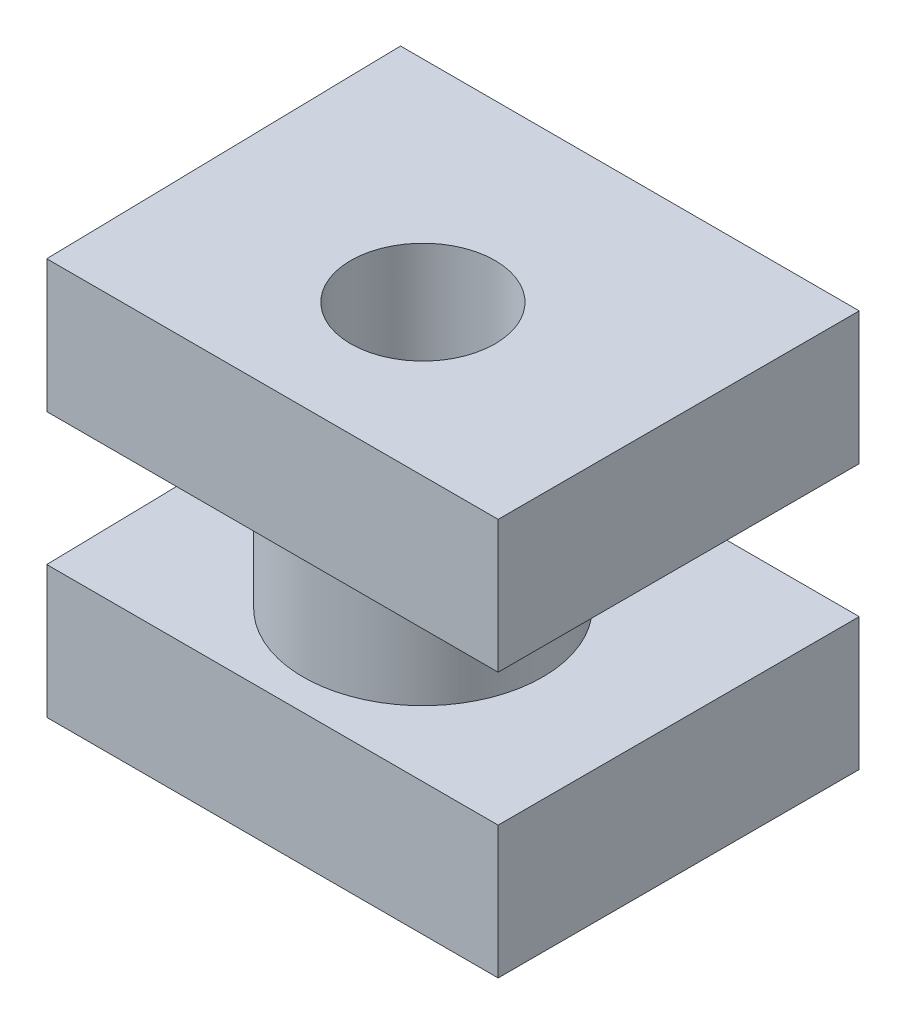
SolidWorks part; units mm, degrees
material "Silicon Rubber"
ref_plane "Front Plane" through (0, 0, 0) normal (0, 0, 1) x (1, 0, 0)
ref_plane "Top Plane" through (0, 0, 0) normal (0, 1, 0) x (1, 0, 0)
ref_plane "Right Plane" through (0, 0, 0) normal (1, 0, 0) x (0, 0, -1)
sketch "Sketch1" plane through (0, 0, 0) normal (0, 1, 0) x (1, 0, 0)
  line L0 (-5.035, 1.3939) -> (-5.035, 3.2473)
  line L1 (-5.035, 3.2473) -> (-7.6675, 3.2473) construction
  line L2 (-5.035, 3.2473) -> (-2.8, 3.2473)
  line L8 (-0.1675, 3.2473) -> (-2.8, 3.2473) construction
  line L9 (-2.8, 3.2473) -> (-2.8, 1.3939)
  line L10 (-3.9175, -0.2527) -> (-3.9175, 3.2473) construction
  line L11 (-0.1675, -2.7527) -> (-0.1675, 3.2473) construction
  line L12 (-7.6675, -2.7527) -> (-7.6675, 3.2473) construction
  line L13 (-0.1675, -2.7527) -> (-7.6675, -2.7527) construction
  line L14 (-7.6675, -0.2527) -> (-7.6675, 3.2473) construction
  line L15 (-5.035, -2.7527) -> (-8.015, -2.7527) construction
  line L16 (-0.1675, -0.2527) -> (-0.1675, 3.2473) construction
  line L18 (-5.035, 3.2473) -> (-8.015, 3.2473) construction
  arc A0 (-5.035, 1.3939) -> (-2.8, 1.3939) centre (-3.9175, -0.2527) ccw
  circle A1 centre (-3.9175, -0.2527) radius 1.2
  dimension "D1" = 3.75
  dimension "D2" = 3.75
  dimension "D3" = 6
extrude "Boss-Extrude1" add sketch "Sketch1" along normal blind 2.2
sketch "Sketch2" plane through (0, 0, 0) normal (0, -1, 0) x (1, 0, 0)
  line L0 (-3.9175, -3.2473) -> (-0.1675, -3.2473)
  line L1 (-2.8, -3.2473) -> (-5.035, -3.2473) construction
  line L2 (-0.1675, -3.2473) -> (-0.1675, 2.7527)
  line L3 (-0.1675, 2.7527) -> (-7.6675, 2.7527)
  line L4 (-7.6675, 2.7527) -> (-7.7899, -3.2473)
  line L5 (-3.9175, -3.2473) -> (-7.7899, -3.2473)
  circle A0 centre (-3.9175, 0.2527) radius 1.2 construction
  circle A1 centre (-3.9175, 0.2527) radius 1.2
extrude "Boss-Extrude2" add sketch "Sketch2" along normal blind 2.2
sketch "Sketch3" plane through (0, 2.2, 0) normal (0, 1, 0) x (1, 0, 0)
  line L0 (-7.7899, 3.2473) -> (-5.035, 3.2473) construction
  line L1 (-7.7899, 3.2473) -> (-5.035, 3.2473)
  line L2 (-7.6675, -2.7527) -> (-7.7899, 3.2473) construction
  line L3 (-7.6675, -2.7527) -> (-7.7899, 3.2473)
  line L4 (-0.1675, -2.7527) -> (-7.6675, -2.7527) construction
  line L5 (-0.1675, -2.7527) -> (-7.6675, -2.7527)
  line L6 (-0.1675, 3.2473) -> (-0.1675, -2.7527) construction
  line L7 (-0.1675, 3.2473) -> (-0.1675, -2.7527)
  line L8 (-2.8, 3.2473) -> (-0.1675, 3.2473) construction
  line L9 (-2.8, 3.2473) -> (-0.1675, 3.2473)
  line L10 (-2.8, 3.2473) -> (-5.035, 3.2473) construction
  line L11 (-2.8, 3.2473) -> (-5.035, 3.2473)
  circle A0 centre (-3.9175, -0.2527) radius 1.2 construction
  circle A1 centre (-3.9175, -0.2527) radius 1.2
extrude "Boss-Extrude3" add sketch "Sketch3" along normal blind 2.2
